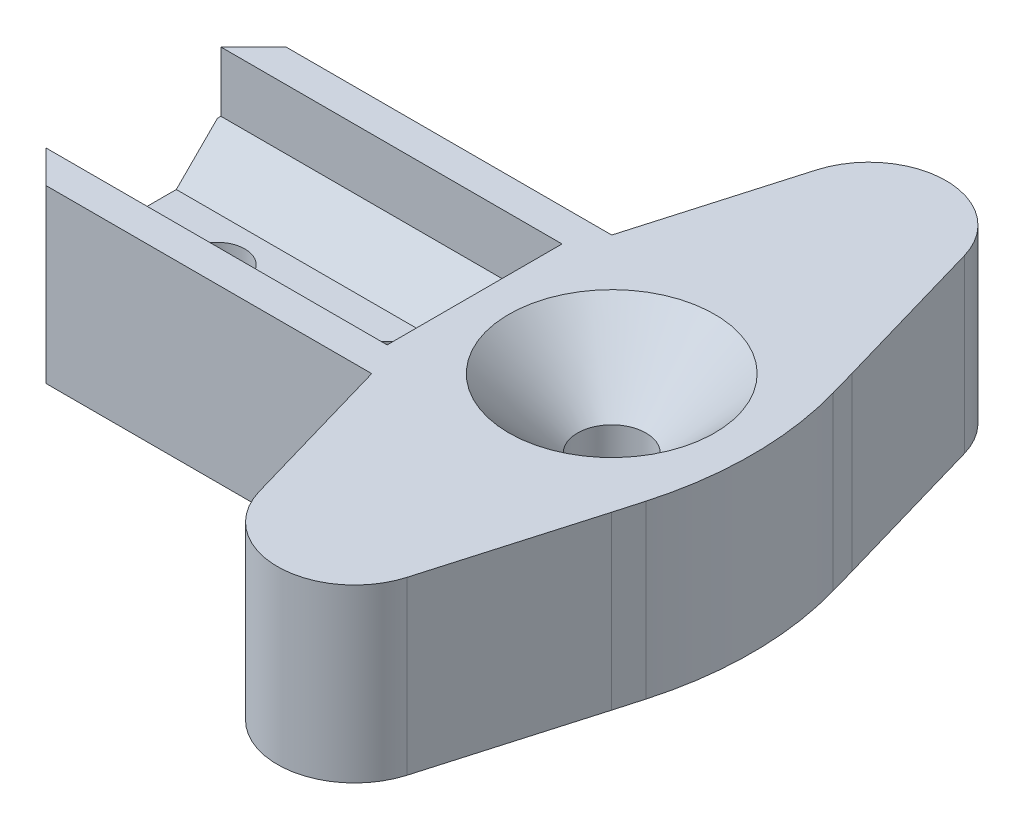
SolidWorks part; units mm, degrees
ref_plane "Plan de face" through (0, 0, 0) normal (0, 0, 1) x (1, 0, 0)
ref_plane "Plan de dessus" through (0, 0, 0) normal (0, 1, 0) x (1, 0, 0)
ref_plane "Plan de droite" through (0, 0, 0) normal (1, 0, 0) x (0, 0, -1)
sketch "Esquisse1" plane through (0, 0, 0) normal (0, 1, 0) x (1, 0, 0)
  line L1 (-28, -7) -> (-7, -7)
  line L2 (-28, -7) -> (-28, 7)
  line L3 (-28, 7) -> (-7, 7)
  line L5 (-28, -7) -> (28, 7) construction
  line L6 (-28, 7) -> (28, -7) construction
  line L8 (-7, 7) -> (-4.3226, 16.251)
  line L9 (7, 7) -> (4.3226, 16.251)
  line L10 (-7, -7) -> (-4.3226, -16.251)
  line L11 (7, -7) -> (4.3226, -16.251)
  line L12 (0, 0) -> (17.9677, 0) construction
  line L13 (7, -7) -> (8.9839, 0)
  line L14 (8.9839, 0) -> (7, 7)
  circle A0 centre (0, 0) radius 2
  arc A2 (4.3226, 16.251) -> (-4.3226, 16.251) centre (0, 15) ccw
  arc A3 (-4.3226, -16.251) -> (4.3226, -16.251) centre (0, -15) ccw
  dimension "D1" = 14
  dimension "D9" = 9
  dimension "D10" = 9
  dimension "D11" = 4
  dimension "D2" = 14
  dimension "D3" = 56
  dimension "D4" = 14
  dimension "D5" = 7
  dimension "D6" = 7
  dimension "D7" = 15
  dimension "D8" = 15
extrude "Boss.-Extru.1" add sketch "Esquisse1" along normal blind 10
sketch "Esquisse2" plane through (-28, 0, 0) normal (-1, 0, 0) x (0, 0, 1)
  line L0 (-7, 10) -> (7, 10) construction
  line L1 (-5.1, 10) -> (5.1, 10)
  line L2 (-5.1, 10) -> (-5.1, 4)
  line L3 (-5.1, 4) -> (5.1, 4)
  line L4 (5.1, 10) -> (5.1, 4)
  line L5 (-7, 0) -> (7, 0) construction
  point P6 (0, 0)
  dimension "D1" = 6
  dimension "D2" = 10.2
  dimension "D3" = 5.1
extrude "Enlèv. mat.-Extru.1" cut sketch "Esquisse2" against normal blind 20
chamfer "Chanfrein1" distance 2.5 angle 45 2 edges at (-18, 4, 5.1) (-18, 4, -5.1)
chamfer "Chanfrein2" distance 1.8 angle 45 3 edges at (-8, 5.25, 3.85) (-8, 4, 0) (-8, 5.25, -3.85)
sketch "Esquisse5" plane through (0, 0, 0) normal (0, -1, 0) x (1, 0, 0)
  line L0 (-32.8926, 0) -> (11.4, 0) construction
  line L2 (-28, -7) -> (-28, 7) construction
  line L3 (24.6, 0) -> (36.0103, 0) construction
  line L4 (14.6, 0) -> (21.4, 0) construction
  circle A0 centre (-23, 0) radius 1.6
  circle A1 centre (-13, 0) radius 1.6
  dimension "D1" = 3.2
  dimension "D2" = 3.2
  dimension "D7" = 10
  dimension "D8" = 5
extrude "Enlèv. mat.-Extru.4" cut sketch "Esquisse5" against normal blind 7
chamfer "Chanfrein4" distance 2.1 angle 45 2 edges at (-23, 0, -1.6) (-13, 0, -1.6)
chamfer "Chanfrein5" distance 2 angle 45 2 edges at (-28, 5, -7) (-28, 5, 7)
sketch "Esquisse6" plane through (0, 0, 0) normal (0, -1, 0) x (1, 0, 0)
  line L0 (-3.9808, -0.3916) -> (-2.5, -15.4447)
  line L1 (3.9799, -0.4) -> (2.4875, -15.25)
  line L2 (-3.9799, 0.4) -> (-2.4875, 15.25)
  line L3 (2.4875, 15.25) -> (3.9799, 0.4)
  arc A0 (-3.9799, 0.4) -> (-3.9808, -0.3916) centre (0, 0) ccw
  arc A1 (2.4875, 15.25) -> (-2.4875, 15.25) centre (0, 15) ccw
  arc A2 (-2.5, -15.4447) -> (2.4875, -15.25) centre (-0.012, -15.2) ccw
  arc A3 (3.9799, -0.4) -> (3.9799, 0.4) centre (0, 0) ccw
  dimension "D3" = 5
  dimension "D4" = 5
  dimension "D5" = 8
  dimension "D1" = 15
  dimension "D2" = 30.2
extrude "Enlèv. mat.-Extru.5" cut sketch "Esquisse6" against normal blind 4
chamfer "Chanfrein6" distance 4 angle 45 1 edges at (0, 10, 2)
fillet "Congé1" radius 20 1 edges at (8.9839, 5, 0)
